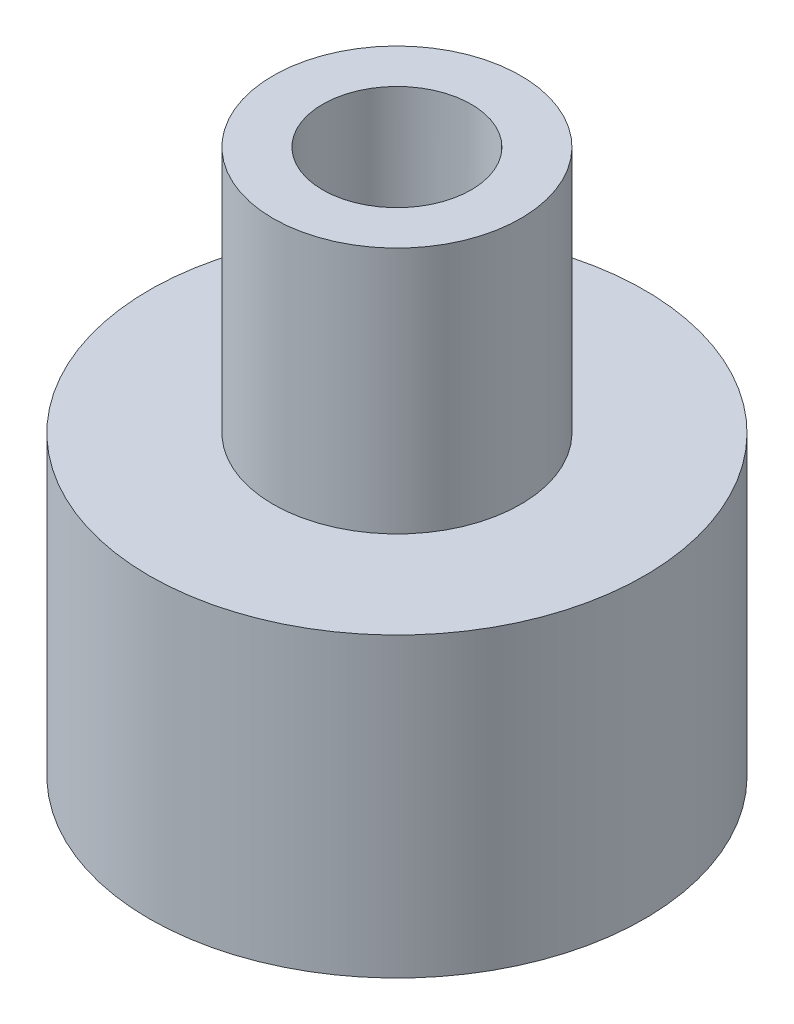
SolidWorks part; units mm, degrees
ref_plane "Front Plane" through (0, 0, 0) normal (0, 0, 1) x (1, 0, 0)
ref_plane "Top Plane" through (0, 0, 0) normal (0, 1, 0) x (1, 0, 0)
ref_plane "Right Plane" through (0, 0, 0) normal (1, 0, 0) x (0, 0, -1)
sketch "Esquisse1" plane through (0, 0, 0) normal (0, 1, 0) x (1, 0, 0)
  circle A0 centre (0, 0) radius 5
extrude "Boss.-Extru.1" add sketch "Esquisse1" along normal blind 6
sketch "Esquisse2" plane through (0, 6, 0) normal (0, 1, 0) x (1, 0, 0)
  circle A0 centre (0, 0) radius 2.5
extrude "Boss.-Extru.2" add sketch "Esquisse2" along normal blind 5 and the other way blind 1
sketch "Esquisse3" plane through (0, 11, 0) normal (0, 1, 0) x (1, 0, 0)
  circle A0 centre (0, 0) radius 1.5
extrude "Enlèv. mat.-Extru.2" cut sketch "Esquisse3" against normal blind 6
sketch "Esquisse4" plane through (0, 0, 0) normal (0, -1, 0) x (1, 0, 0)
  circle A0 centre (0, 0) radius 2.55
extrude "Enlèv. mat.-Extru.3" cut sketch "Esquisse4" against normal blind 5
